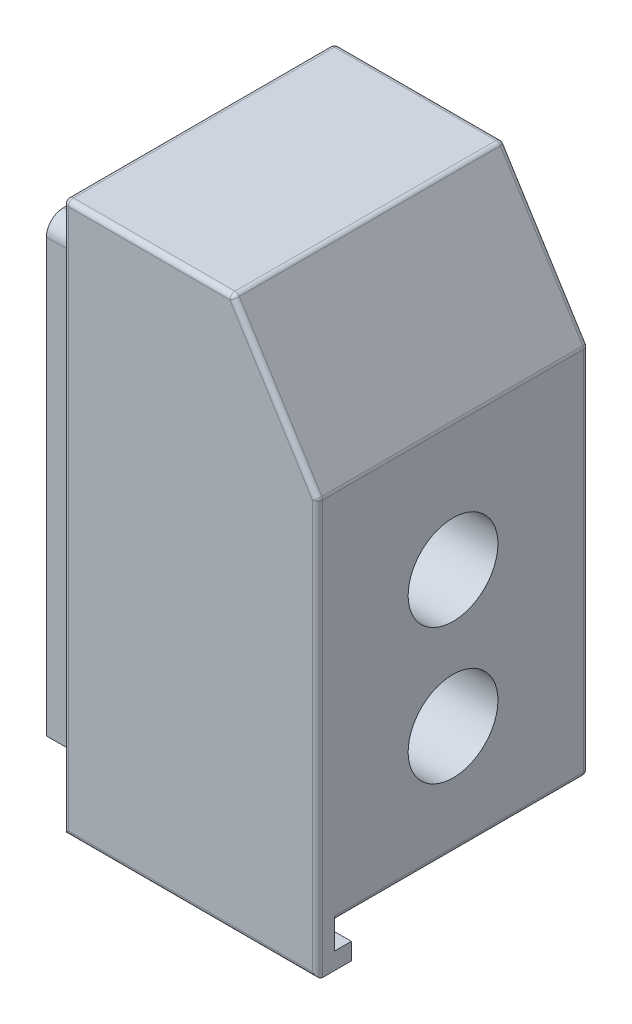
SolidWorks part; units mm, degrees
ref_plane "Ön Düzlem" through (0, 0, 0) normal (0, 0, 1) x (1, 0, 0)
ref_plane "Üst Düzlem" through (0, 0, 0) normal (0, 1, 0) x (1, 0, 0)
ref_plane "Sağ Düzlem" through (0, 0, 0) normal (1, 0, 0) x (0, 0, -1)
sketch "Sketch1" plane through (0, 0, 0) normal (0, 0, 1) x (1, 0, 0)
  line L0 (0, 0) -> (0, 30)
  line L1 (0, 30) -> (10, 30)
  line L2 (10, 30) -> (15, 22)
  line L3 (15, 22) -> (15, 0)
  line L4 (15, 0) -> (0, 0)
  dimension "D1" = 30
  dimension "D2" = 15
  dimension "D3" = 10
  dimension "D4" = 22
extrude "Boss-Extrude1" add sketch "Sketch1" along normal blind 16
sketch "Sketch3" plane through (15, 0, 0) normal (1, 0, 0) x (0, 0, -1)
  line L0 (-16, 0) -> (-16, -2.5)
  line L1 (-16, -2.5) -> (-14, -2.5)
  line L2 (-15, 0) -> (-15, -1.5)
  line L3 (-15, -1.5) -> (-14, -1.5)
  line L4 (-16, 0) -> (0, 0) construction
  line L5 (-14, -1.5) -> (-14, -2.5)
  line L6 (-16, 0) -> (-15, 0)
  dimension "D2" = 1.5
  dimension "D3" = 1
  dimension "D1" = 1
extrude "Boss-Extrude2" add sketch "Sketch3" against normal up to surface (15 mm away) up to face at (0, 15, 8)
sketch "Sketch4" plane through (15, 0, 0) normal (1, 0, 0) x (0, 0, -1)
  line L0 (-8, -0.0014) -> (-8, 22) construction
  line L2 (-16, 22) -> (0, 22) construction
  circle A0 centre (-8, 14.5) radius 2.65
  circle A1 centre (-8, 6.5) radius 2.65
  dimension "D1" = 5.3
  dimension "D2" = 8
  dimension "D3" = 6.5
extrude "Cut-Extrude1" cut sketch "Sketch4" against normal through all
sketch "Sketch6" plane through (0, 0, 0) normal (-1, 0, 0) x (0, 0, 1)
  line L0 (16, 30) -> (0, 30) construction
  line L1 (15, 27.5) -> (1, 27.5)
  line L2 (15, 27.5) -> (15, 1)
  line L3 (15, 1) -> (1, 1)
  line L4 (1, 27.5) -> (1, 1)
  line L5 (15, 27.5) -> (1, 1) construction
  line L6 (15, 1) -> (1, 27.5) construction
  line L7 (16, 30) -> (16, -2.5) construction
  line L8 (0, 30) -> (0, 0) construction
  line L9 (15, 0) -> (0, 0) construction
  point P0 (8, 14.25)
  dimension "D1" = 2.5
  dimension "D2" = 1
  dimension "D3" = 1
  dimension "D4" = 1
extrude "Boss-Extrude4" add sketch "Sketch6" along normal blind 2 separate body
fillet "Fillet3" radius 1 2 edges at (-1, 27.5, 15) (-1, 27.5, 1)
fillet "Fillet4" radius 0.3 14 edges at (0, 15, 0) (7.5, 0, 0) (7.5, -2.5, 16) (0, 13.75, 16) (15, 9.75, 16) (15, 11, 0) (15, 22, 8) (12.5, 26, 16) (12.5, 26, 0) (10, 30, 8) (5, 30, 16) (0, 30, 8) (5, 30, 0)
